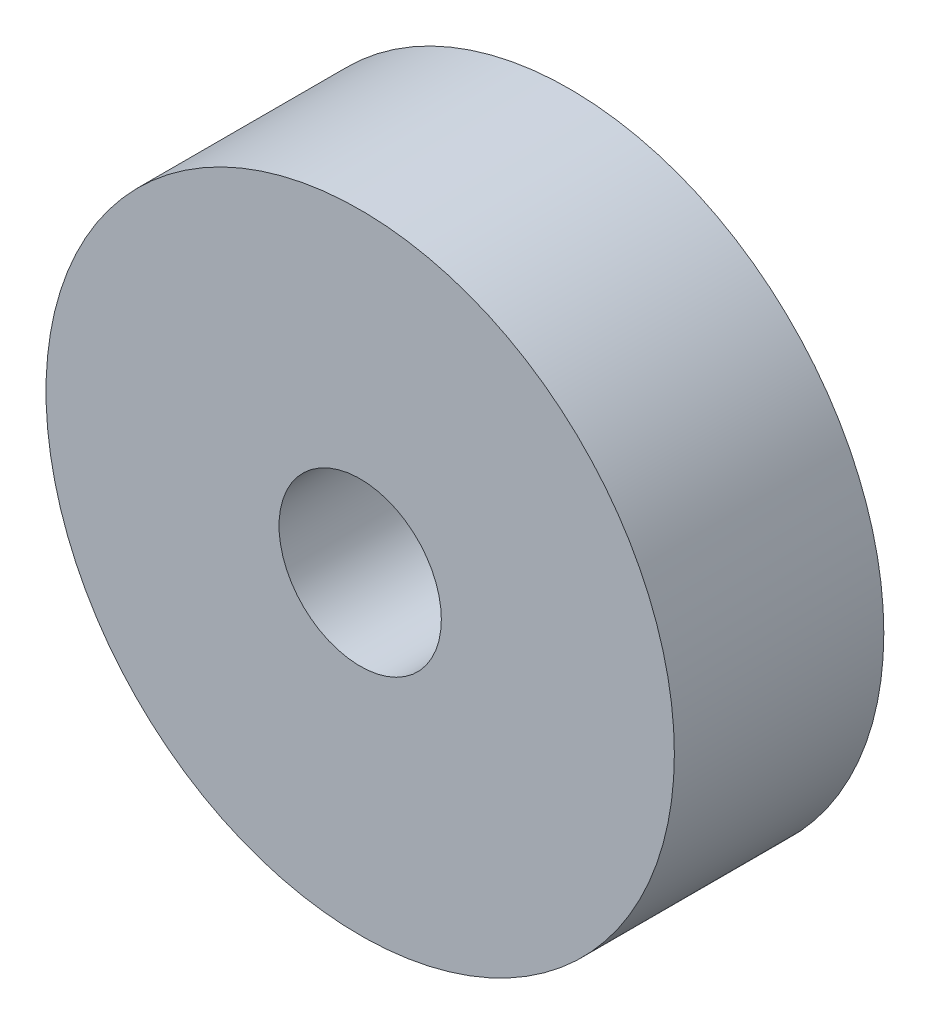
SolidWorks part; units mm, degrees
material "Thornel Mat VMA"
ref_plane "前视基准面" through (0, 0, 0) normal (0, 0, 1) x (1, 0, 0)
ref_plane "上视基准面" through (0, 0, 0) normal (0, 1, 0) x (1, 0, 0)
ref_plane "右视基准面" through (0, 0, 0) normal (1, 0, 0) x (0, 0, -1)
sketch "草图1" plane through (0, 0, 0) normal (0, 0, 1) x (1, 0, 0)
  circle A0 centre (0, 0) radius 1.55
  circle A1 centre (0, 0) radius 6
  dimension "D1" = 3.1
  dimension "D2" = 12
extrude "凸台-拉伸1" add sketch "草图1" along normal blind 4
